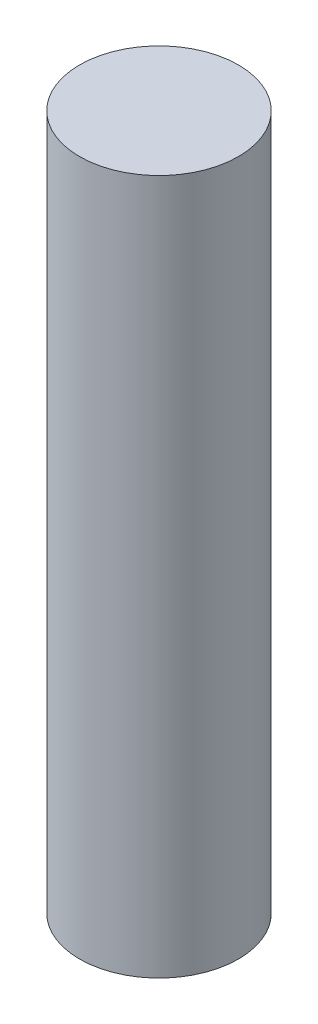
SolidWorks part; units mm, degrees
material "7075-T6 (SN)"
ref_plane "前视基准面" through (0, 0, 0) normal (0, 0, 1) x (1, 0, 0)
ref_plane "上视基准面" through (0, 0, 0) normal (0, 1, 0) x (1, 0, 0)
ref_plane "右视基准面" through (0, 0, 0) normal (1, 0, 0) x (0, 0, -1)
other "Configuration Table"
sketch "草图1" plane through (0, 0, 0) normal (0, 1, 0) x (1, 0, 0)
  circle A0 centre (0, 0) radius 4
  dimension "D1" = 8
extrude "凸台-拉伸1" add sketch "草图1" along normal blind 35
